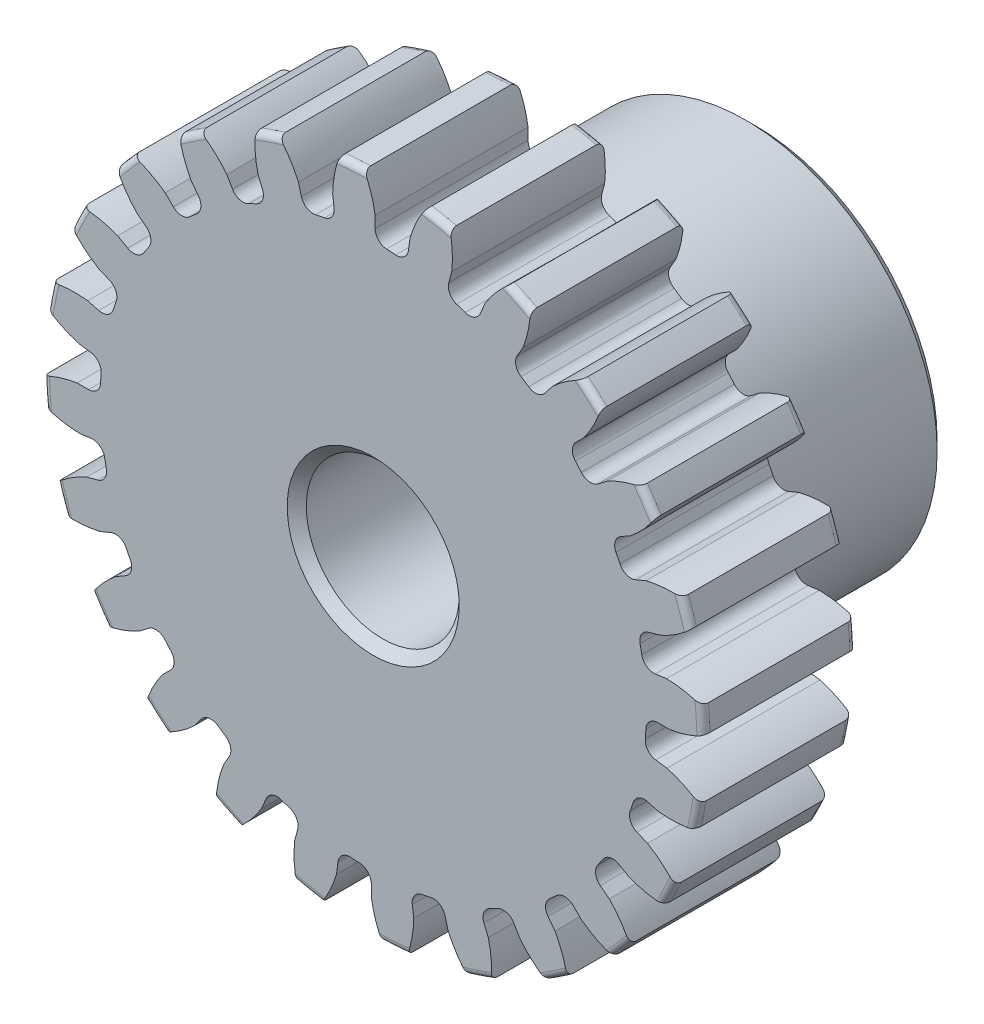
SolidWorks part; units mm, degrees
ref_plane "Front" through (0, 0, 0) normal (0, 0, 1) x (1, 0, 0)
ref_plane "Top" through (0, 0, 0) normal (0, 1, 0) x (1, 0, 0)
ref_plane "Right" through (0, 0, 0) normal (1, 0, 0) x (0, 0, -1)
sketch "Sketch1" plane through (0, 0, 0) normal (0, 0, 1) x (1, 0, 0)
  line L0 (-304.8, 0) -> (304.8, 0) construction
  circle A0 centre (0, 0) radius 13.716
  circle A1 centre (0, 0) radius 12.7 construction
  circle A3 centre (0, 0) radius 11.3348 construction
  dimension "D1" = 2.3812
  dimension "OD" = 27.432
  dimension "Ptich Dia" = 25.4
  dimension "Root Dia" = 22.6695
  dimension "D3" = 1.016
  dimension "Number of Teeth" = 609.6
extrude "Boss-Extrude1" add sketch "Sketch1" against normal blind 6.35
sketch "Sketch2" plane through (0, 0, 0) normal (1, 0, 0) x (0, 0, -1)
  line L0 (6.35, 0) -> (15.875, 0)
  line L1 (6.35, 0) -> (6.35, 7.9375)
  line L2 (6.35, 7.9375) -> (15.875, 7.9375)
  line L3 (15.875, 7.9375) -> (15.875, 0)
  point P5 (15.875, -7.9375)
  point P6 (0, -13.716)
  point P7 (6.35, -13.716)
  point P9 (0, 13.716)
  dimension "Face Wd" = 6.35
  dimension "B Hub Dia" = 15.875
  dimension "D O'all Lg." = 15.875
revolve "Revolve1" add sketch "Sketch2" angle 360 about L0
fillet "Fillet2" radius 0.2743 3 edges at (13.716, 0, -6.35) (13.716, 0, 0) (7.9375, 0, -6.35)
sketch "Sketch3" plane through (0, 0, 0) normal (0, 0, 1) x (1, 0, 0)
  line L0 (0, 0) -> (0, 13.716) construction
  line L1 (-3.0785, 11.9038) -> (0, 12.7)
  line L2 (-9.5921, 12.7) -> (9.5921, 12.7) construction
  line L3 (-9.2865, 10.2983) -> (9.2865, 15.1017) construction
  line L4 (-3.0785, 11.9038) -> (0, 0) construction
  line L5 (-7.8523, 9.4615) -> (0, 0) construction
  line L6 (-7.8523, 9.4615) -> (-1.2652, 14.9283) construction
  line L7 (-2.1466, 12.1066) -> (0, 0) construction
  line L8 (-2.1466, 12.1066) -> (0.045, 12.4952) construction
  arc A0 (-3.0785, 11.9038) -> (-7.8523, 9.4615) centre (0, 0) ccw
  circle A1 centre (0, 0) radius 12.7 construction
  circle A2 centre (0, 0) radius 12.2955 construction
  arc A3 (-3.0785, 11.9038) -> (-2.1466, 12.1066) centre (0, 0) cw
  circle A4 centre (0, 0) radius 13.716 construction
  point P6 (0, 12.7)
  dimension "D1" = 3.1798
  dimension "Pressure Angle" = 14.5
  dimension "D2" = 5.4057
  dimension "D3" = 8.5601
  dimension "D4" = 0.9539
  dimension "D5" = 2.2259
sketch "Sketch4" plane through (0, 0, 0) normal (0, 0, 1) x (1, 0, 0)
  line L0 (0, 0) -> (0.8288, 12.6457) construction
  line L1 (0.0798, 12.2952) -> (0.0798, 11.3345)
  line L2 (0, 12.7) -> (1.6577, 12.5913) construction
  line L3 (1.5257, 12.2004) -> (1.4003, 11.2479)
  line L4 (0.0798, 11.3345) -> (0, 0) construction
  line L5 (0, 0) -> (0, 13.716) construction
  line L6 (-7.8523, 9.4615) -> (-1.2652, 14.9283) construction
  line L7 (-7.8523, 9.4615) -> (-1.2652, 14.9283) construction
  arc A0 (1.4003, 11.2479) -> (0.0798, 11.3345) centre (0, 0) ccw
  arc A1 (0, 12.7) -> (1.6577, 12.5913) centre (0, 0) cw construction
  circle A2 centre (0, 0) radius 12.7 construction
  circle A3 centre (0, 0) radius 12.2955 construction
  circle A4 centre (0, 0) radius 11.3347 construction
  arc A5 (3.2029, 14.6354) -> (-1.2652, 14.9283) centre (0, 0) ccw
  spline S0 degree 2 poles (-1.2652, 14.9283) (-0.1435, 13.7672) (0.0798, 12.2952) knots 0 0 0 1 1 1
  spline S1 degree 2 poles (3.2029, 14.6354) (1.9392, 13.6307) (1.5257, 12.2004) knots 0 0 0 1 1 1
  dimension "D1" = 1.6624
extrude "Cut-Extrude1" cut sketch "Sketch4" against normal through all
fillet "Fillet1" radius 0.4987 2 edges at (1.4003, 11.2479, -3.175) (0.0798, 11.3345, -3.175)
pattern_circular "CirPattern1" count 24 over 360 about axis through (0, 0, -6.35) along (0, 0, 1) of "Cut-Extrude1", "Fillet1"
sketch "Sketch5" plane through (0, 0, 0) normal (0, 0, 1) x (1, 0, 0)
  circle A0 centre (0, 0) radius 3.175
  circle A1 centre (0, 0) radius 1.5875 construction
  dimension "Bore Min" = 6.35
  dimension "Bore Max" = 3.175
extrude "Cut-Extrude2" cut sketch "Sketch5" against normal through all
chamfer "Chamfer1" distance 0.3969 angle 45 3 edges at (7.9375, 0, -15.875) (3.175, 0, 0) (3.175, 0, -15.875)
sketch "Pitch Dia" plane through (0, 0, 0) normal (0, 0, 1) x (1, 0, 0)
  circle A0 centre (0, 0) radius 12.7 construction
  circle A1 centre (0, 0) radius 12.7 construction
equation "\"D1@Boss-Extrude1\" = \"Face Wd@Sketch2\""
equation "\"D2@Sketch3\" = \"D1@Sketch3\"*1.7"
equation "\"D3@Sketch3\" = \"D1@Sketch3\"+\"D2@Sketch3\"-.001"
equation "\"D4@Sketch3\" = \"D1@Sketch3\"*.3"
equation "\"D5@Sketch3\" = \"D1@Sketch3\"-\"D4@Sketch3\""
equation "\"D1@Sketch4\" = 1.5708/(\"Number of Teeth@Sketch1\"/\"Ptich Dia@Sketch1\")"
equation "\"D1@Chamfer1\" = \"B Hub Dia@Sketch2\"*.025"
equation "\"D1@CirPattern1\" = \"Number of Teeth@Sketch1\""
equation "\"D1@Fillet1\" = \"D1@Sketch4\"*.3"
equation "\"D1@Fillet2\" = \"OD@Sketch1\"*.01"
equation "\"D1@Sketch1\" = 2.250/(\"Number of Teeth@Sketch1\"/\"Ptich Dia@Sketch1\")"
